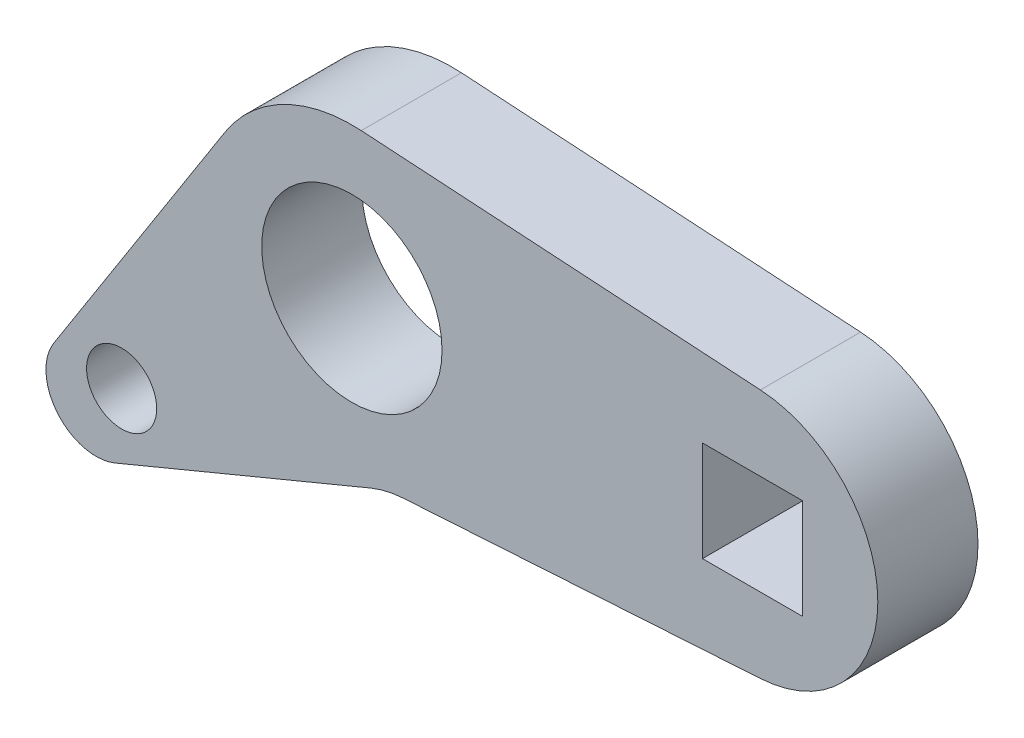
SolidWorks part; units mm, degrees
ref_plane "Спереди" through (0, 0, 0) normal (0, 0, 1) x (1, 0, 0)
ref_plane "Сверху" through (0, 0, 0) normal (0, 1, 0) x (1, 0, 0)
ref_plane "Справа" through (0, 0, 0) normal (1, 0, 0) x (0, 0, -1)
sketch "Эскиз1" plane through (0, 0, 0) normal (0, 0, 1) x (1, 0, 0)
  line L0 (40, 0) -> (0, 0) construction
  line L1 (0, 0) -> (-22.9813, -19.2836) construction
  line L2 (-38.3022, -32.1394) -> (-12.6449, 8.0689)
  line L3 (-38.3022, -32.1394) -> (5.7505, -13.8539)
  line L4 (0.9375, 14.9707) -> (40.7812, 12.4756)
  line L5 (40.7812, -12.4756) -> (0.9375, -14.9707)
  line L7 (35, -5) -> (45, -5)
  line L8 (35, -5) -> (35, 5)
  line L9 (35, 5) -> (45, 5)
  line L10 (45, -5) -> (45, 5)
  line L11 (35, -5) -> (45, 5) construction
  line L12 (35, 5) -> (45, -5) construction
  circle A0 centre (0, 0) radius 15
  circle A1 centre (40, 0) radius 12.5
  circle A2 centre (-22.9813, -19.2836) radius 6
  circle A3 centre (0, 0) radius 9
  circle A4 centre (-22.9813, -19.2836) radius 3.5
  dimension "D1" = 30
  dimension "D2" = 25
  dimension "D6" = 12
  dimension "D7" = 18
  dimension "D9" = 7
  dimension "D3" = 40
  dimension "D4" = 30
  dimension "D5" = 140
  dimension "D8" = 10
extrude "Бобышка-Вытянуть1" add sketch "Эскиз1" along normal blind 10 contours A2 L3 L5 A0 L2 | A2 A4 | A2 L2 L3 | A0 A3 | A1 L4 A0 L3 L5 | A1 L10 L7 L8 L9 | A0 L5 L3
fillet "Скругление1" radius 5 1 edges at (-38.3022, -32.1394, 5)
fillet "Скругление2" radius 10 1 edges at (3.4372, -14.8141, 5)
